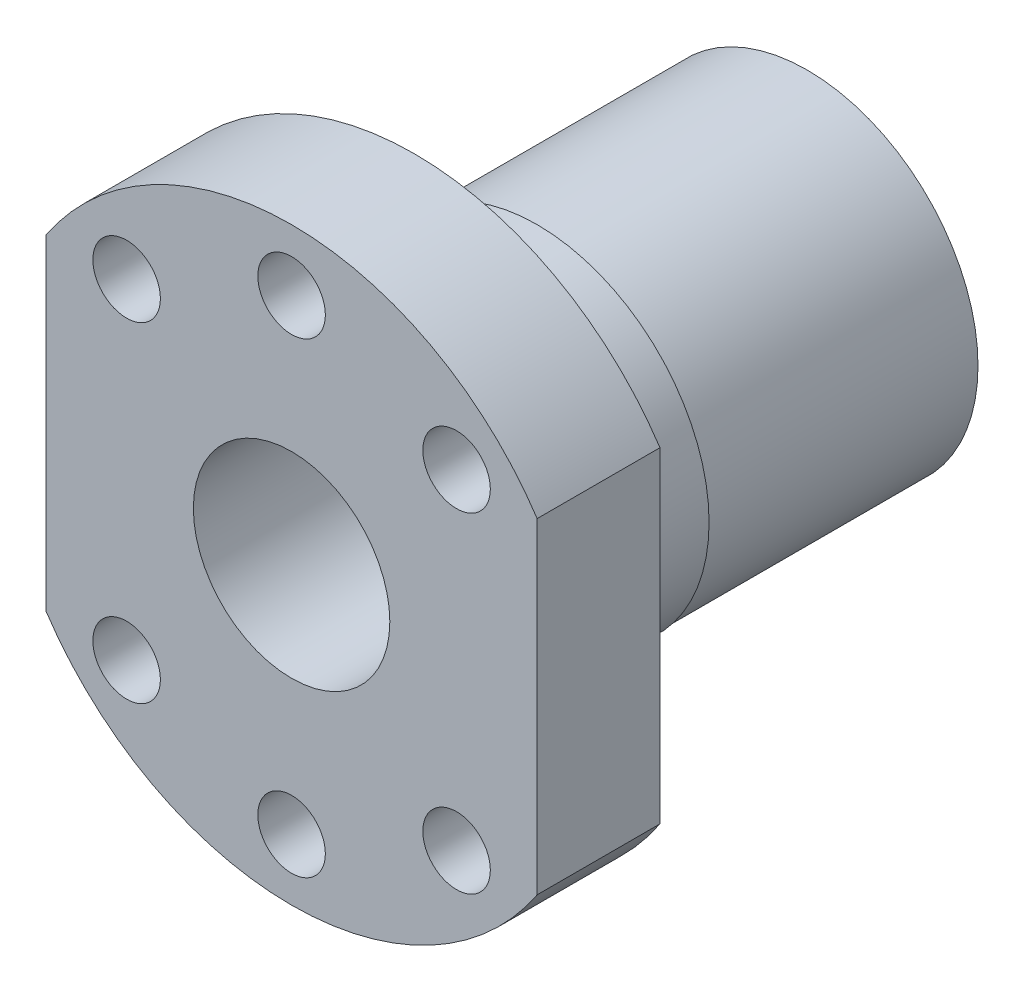
SolidWorks part; units mm, degrees
ref_plane "정면" through (0, 0, 0) normal (0, 0, 1) x (1, 0, 0)
ref_plane "윗면" through (0, 0, 0) normal (0, 1, 0) x (1, 0, 0)
ref_plane "우측면" through (0, 0, 0) normal (1, 0, 0) x (0, 0, -1)
sketch "스케치1" plane through (0, 0, 0) normal (0, 0, 1) x (1, 0, 0)
  circle A0 centre (0, 0) radius 24
  dimension "D1" = 48
extrude "보스-돌출1" add sketch "스케치1" along normal blind 10
sketch "스케치2" plane through (0, 0, 0) normal (0, 0, -1) x (-1, 0, 0)
  circle A0 centre (0, 0) radius 14
  dimension "D1" = 28
extrude "보스-돌출2" add sketch "스케치2" along normal blind 10
sketch "스케치3" plane through (0, 0, -10) normal (0, 0, -1) x (-1, 0, 0)
  circle A0 centre (0, 0) radius 13.9
  dimension "D1" = 27.8
extrude "보스-돌출3" add sketch "스케치3" along normal blind 22
sketch "스케치4" plane through (0, 0, 10) normal (0, 0, 1) x (1, 0, 0)
  line L0 (-20, 13.2665) -> (-20, -13.2665)
  line L1 (20, 13.2665) -> (20, -13.2665)
  circle A0 centre (0, 0) radius 24 construction
  arc A1 (-20, 13.2665) -> (20, 13.2665) centre (0, 0) cw
  arc A2 (-20, -13.2665) -> (20, -13.2665) centre (0, 0) ccw
  circle M3 centre (0, 0) radius 24
  dimension "D1" = 40
  dimension "D2" = 20
extrude "컷-돌출1" cut sketch "스케치4" against normal blind 22 contours L1 M3 | L0 M3
sketch "스케치5" plane through (0, 0, 10) normal (0, 0, 1) x (1, 0, 0)
  line L0 (0, 31.1609) -> (0, -31.1609) construction
  line L1 (0, 0) -> (-13.435, 13.435) construction
  line L2 (13.435, 13.435) -> (0, 0) construction
  line L3 (-21.8935, 0) -> (26.5612, 0) construction
  circle A0 centre (0, 19) radius 2.75
  circle A1 centre (-13.435, 13.435) radius 2.75
  circle A2 centre (13.435, 13.435) radius 2.75
  circle A3 centre (0, 0) radius 19
  arc A4 (-20, -13.2665) -> (20, -13.2665) centre (0, 0) ccw construction
  circle A5 centre (13.435, -13.435) radius 2.75
  circle A6 centre (0, -19) radius 2.75
  circle A7 centre (-13.435, -13.435) radius 2.75
  dimension "D1" = 38
  dimension "D5" = 5.5
  dimension "D6" = 5.5
  dimension "D7" = 5.5
  dimension "D2" = 45
  dimension "D3" = 45
  dimension "D4" = 0
extrude "컷-돌출2" cut sketch "스케치5" against normal blind 22 contours A7 A3 | A7 A3 | A6 A3 | A6 A3 | A5 A3 | A5 A3 | A3 A2 | A2 A3 | A3 A0 | A0 A3 | A3 A1 | A1 A3
sketch "스케치6" plane through (0, 0, 10) normal (0, 0, 1) x (1, 0, 0)
  circle A0 centre (0, 0) radius 8
  dimension "D1" = 16
extrude "컷-돌출3" cut sketch "스케치6" against normal through all
